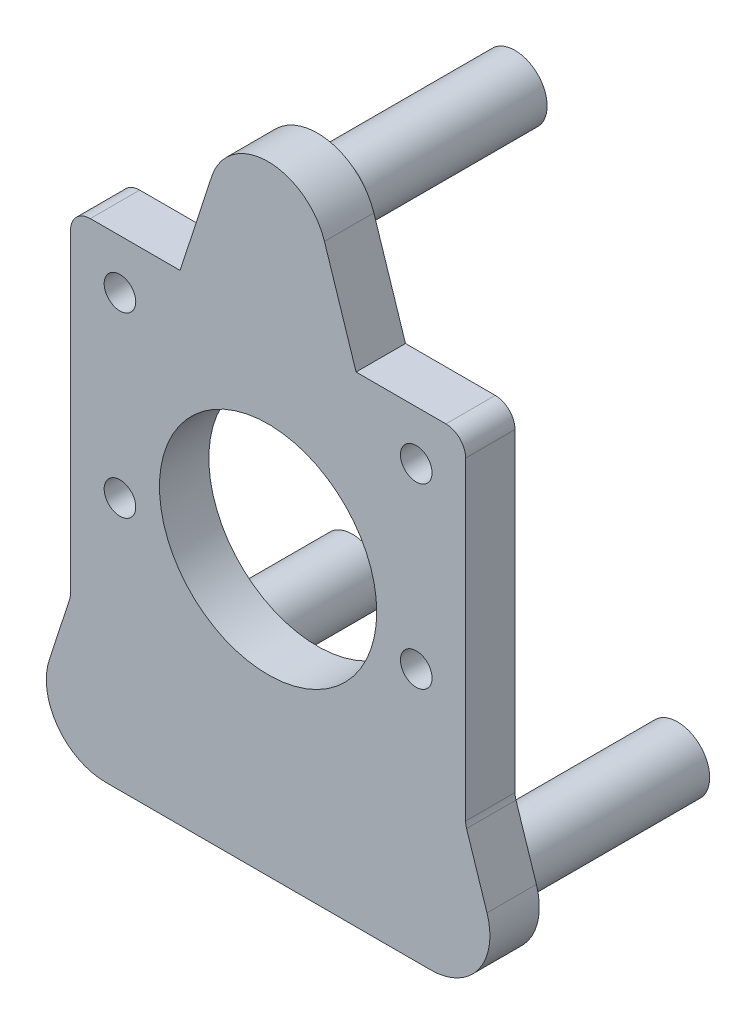
SolidWorks part; units mm, degrees
ref_plane "前视基准面" through (0, 0, 0) normal (0, 0, 1) x (1, 0, 0)
ref_plane "上视基准面" through (0, 0, 0) normal (0, 1, 0) x (1, 0, 0)
ref_plane "右视基准面" through (0, 0, 0) normal (1, 0, 0) x (0, 0, -1)
other "Configuration Table"
sketch "草图1" plane through (0, 0, 0) normal (0, 0, 1) x (1, 0, 0)
  line L0 (-5.7063, 29.8541) -> (-22.1643, -20.7984)
  line L1 (-16.458, -28.6525) -> (16.458, -28.6525)
  line L2 (0, -26.4) -> (0, 26.4) construction
  line L3 (5.7063, 29.8541) -> (22.1643, -20.7984)
  circle A0 centre (0, 0) radius 28 construction
  arc A1 (5.7063, 29.8541) -> (-5.7063, 29.8541) centre (0, 28) ccw
  circle A2 centre (26.6296, 8.6525) radius 6 construction
  arc A3 (16.458, -28.6525) -> (22.1643, -20.7984) centre (16.458, -22.6525) ccw
  arc A4 (-22.1643, -20.7984) -> (-16.458, -28.6525) centre (-16.458, -22.6525) ccw
  circle A5 centre (-26.6296, 8.6525) radius 6 construction
  circle A6 centre (0, 0) radius 11
  point P15 (0, 0)
  dimension "D1" = 56
  dimension "D2" = 12
  dimension "D4" = 22
  dimension "D3" = 5
extrude "凸台-拉伸1" add sketch "草图1" along normal blind 5
sketch "草图2" plane through (0, 0, 0) normal (0, 0, -1) x (-1, 0, 0)
  circle A0 centre (0, 28) radius 3.25
  circle A1 centre (-16.458, -22.6525) radius 3.25
  circle A2 centre (16.458, -22.6525) radius 3.25
  dimension "D1" = 6.5
  dimension "D2" = 6.5
  dimension "D3" = 6.5
extrude "凸台-拉伸2" add sketch "草图2" along normal blind 20
fillet "圆角1" radius 2 3 edges at (-13.208, -22.6525, 0) (19.708, -22.6525, 0) (3.25, 28, 0)
sketch "草图3" plane through (0, 0, 5) normal (0, 0, 1) x (1, 0, 0)
  line L0 (0, -2.75) -> (0, 2.75) construction
  line L1 (-20, 20) -> (-8.9081, 20)
  line L2 (-20, 20) -> (-20, -14.1373)
  line L4 (20, 20) -> (20, -14.1373)
  line L5 (-5.7063, 29.8541) -> (-22.1643, -20.7984) construction
  line L6 (-8.9081, 20) -> (-20, -14.1373)
  line L7 (22.1643, -20.7984) -> (5.7063, 29.8541) construction
  line L8 (20, -14.1373) -> (8.9081, 20)
  line L9 (8.9081, 20) -> (20, 20)
  circle A0 centre (-15, 15) radius 1.6 construction
  circle A1 centre (0, 0) radius 11 construction
  circle A2 centre (15, 15) radius 1.6 construction
  point P6 (-20, -8)
  point P21 (20, -14.1373)
  point P22 (19.8726, -13.7453)
  point P23 (-20, -14.1373)
  point P24 (-20, -8)
  point P25 (-20, -13.7039)
  dimension "D1" = 3.2
  dimension "D2" = 15
  dimension "D3" = 15
  dimension "D4" = 5
  dimension "D5" = 5
  dimension "D7" = 5
extrude "凸台-拉伸3" add sketch "草图3" against normal blind 5
fillet "圆角2" radius 2 4 edges at (20, -14.1373, 2.5) (-20, -14.1373, 2.5) (20, 20, 2.5) (-20, 20, 2.5)
sketch "草图4" plane through (0, 0, 5) normal (0, 0, 1) x (1, 0, 0)
  line L0 (-15, 15) -> (15, 15) construction
  line L1 (-15, 15) -> (-15, -3) construction
  circle A0 centre (-15, 15) radius 1.6
  circle A1 centre (15, 15) radius 1.6
  circle A2 centre (15, -3) radius 1.6
  circle A3 centre (-15, -3) radius 1.6
  dimension "D1" = 3.2
  dimension "D2" = 15
  dimension "D3" = 15
  dimension "D6" = 90
  dimension "D7" = 30
  dimension "D4" = 2
  dimension "D5" = 2
extrude "切除-拉伸1" cut sketch "草图4" against normal blind 5
